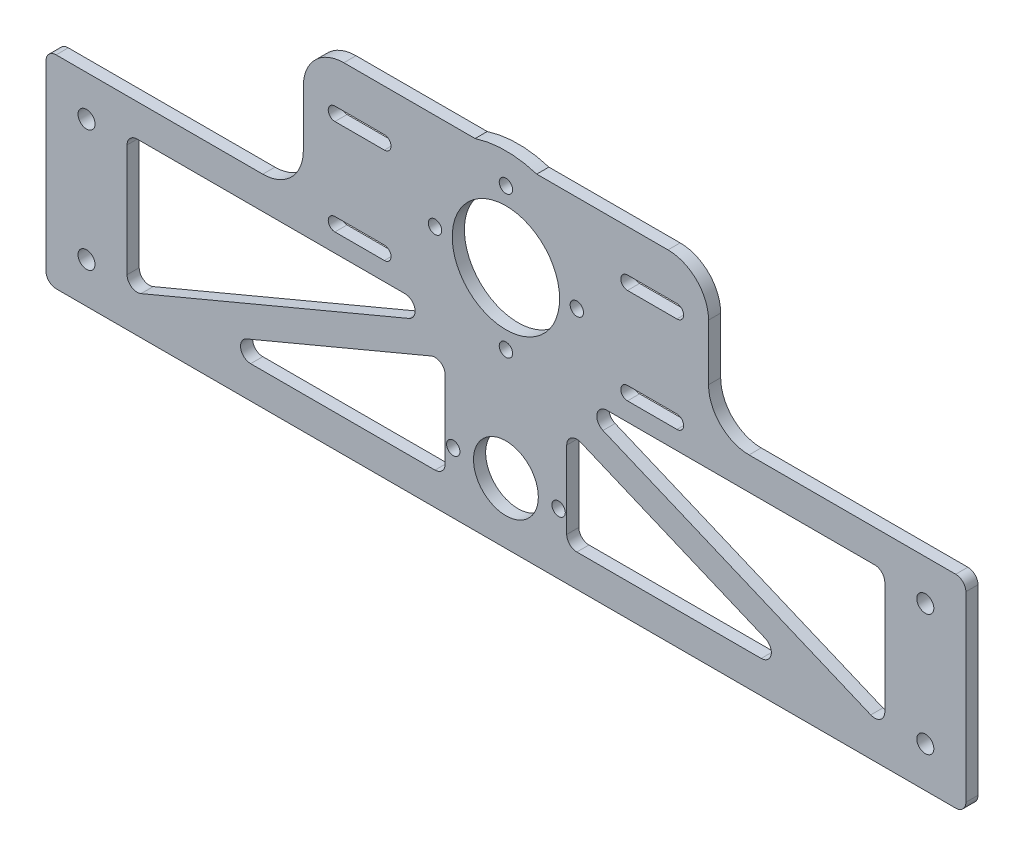
SolidWorks part; units mm, degrees
material "6061 合金"
ref_plane "前视基准面" through (0, 0, 0) normal (0, 0, 1) x (1, 0, 0)
ref_plane "上视基准面" through (0, 0, 0) normal (0, 1, 0) x (1, 0, 0)
ref_plane "右视基准面" through (0, 0, 0) normal (1, 0, 0) x (0, 0, -1)
sketch "草图1" plane through (0, 0, 0) normal (0, 0, 1) x (1, 0, 0)
  line L0 (7.6049, 23.8152) -> (113.5, -10) construction
  line L1 (113.5, -10) -> (113.5, -60)
  line L3 (0, 17.5) -> (0, -70.2013) construction
  line L4 (103.5, -6.8067) -> (103.5, -60) construction
  line L5 (113.5, -35) -> (103.5, -35) construction
  line L6 (-113.5, -35) -> (-103.5, -35) construction
  line L7 (-103.5, -6.8067) -> (-103.5, -60) construction
  line L9 (-113.5, -10) -> (-113.5, -60)
  line L10 (-7.6049, 23.8152) -> (-113.5, -10) construction
  line L11 (-113.5, -10) -> (-50, -10)
  line L12 (-50, -10) -> (-50, 23.8152)
  line L13 (-50, 23.8152) -> (-7.6049, 23.8152)
  line L14 (50, 23.8152) -> (7.6049, 23.8152)
  line L15 (113.5, -10) -> (50, -10)
  line L16 (50, -10) -> (50, 23.8152)
  line L17 (-113.5, -60) -> (113.5, -60)
  circle A0 centre (0, 0) radius 17.5 construction
  circle A1 centre (0, 0) radius 13.25
  circle A2 centre (0, 17.5) radius 1.65
  circle A3 centre (-17.5, 0) radius 1.65
  circle A4 centre (0, -17.5) radius 1.65
  circle A5 centre (17.5, 0) radius 1.65
  arc A6 (7.6049, 23.8152) -> (-7.6049, 23.8152) centre (0, 0) ccw
  circle A7 centre (103.5, -20) radius 2.1
  circle A8 centre (103.5, -50) radius 2.1
  circle A10 centre (0, -45) radius 8
  circle A11 centre (-103.5, -50) radius 2.1
  circle A12 centre (-103.5, -20) radius 2.1
  dimension "D1" = 26.5
  dimension "D2" = 35
  dimension "D3" = 3.3
  dimension "D4" = 4.2
  dimension "D6" = 30
  dimension "D8" = 50
  dimension "D10" = 83.8152
  dimension "D11" = 16
  dimension "D12" = 15
  dimension "D5" = 10
  dimension "D7" = 50
  dimension "D9" = 227
  dimension "D14" = 100
extrude "凸台-拉伸1" add sketch "草图1" along normal blind 3
fillet "圆角1" radius 10 4 edges at (50, -10, 1.5) (50, 23.8152, 1.5) (-50, -10, 1.5) (-50, 23.8152, 1.5)
sketch "草图2" plane through (0, 0, 3) normal (0, 0, 1) x (1, 0, 0)
  line L0 (-93.5, -18) -> (-93.5, -52)
  line L1 (-93.5, -52) -> (-12.5, -18)
  line L2 (-12.5, -18) -> (-93.5, -18)
  line L7 (0, 25) -> (0, -75) construction
  line L8 (12.5, -18) -> (93.5, -18)
  line L9 (93.5, -52) -> (12.5, -18)
  line L10 (93.5, -18) -> (93.5, -52)
  line L12 (113.5, -60) -> (113.5, -10) construction
  line L13 (-75.414, -52) -> (-15, -26.6411)
  line L14 (-15, -26.6411) -> (-15, -52)
  line L15 (-15, -52) -> (-75.414, -52)
  line L16 (15, -52) -> (75.414, -52)
  line L17 (15, -26.6411) -> (15, -52)
  line L18 (75.414, -52) -> (15, -26.6411)
  line L19 (113.5, -10) -> (60, -10) construction
  arc A0 (7.6049, 23.8152) -> (-7.6049, 23.8152) centre (0, 0) ccw construction
  dimension "D4" = 7
  dimension "D1" = 8
  dimension "D2" = 20
  dimension "D3" = 25
  dimension "D5" = 34
  dimension "D6" = 30
extrude "切除-拉伸1" cut sketch "草图2" against normal blind 3
fillet "圆角3" radius 2.5 16 edges at (-113.5, -10, 1.5) (113.5, -10, 1.5) (12.5, -18, 1.5) (93.5, -52, 1.5) (93.5, -18, 1.5) (-93.5, -18, 1.5) (-12.5, -18, 1.5) (-93.5, -52, 1.5) (113.5, -60, 1.5) (-113.5, -60, 1.5) (75.414, -52, 1.5) (15, -26.6411, 1.5) (15, -52, 1.5) (-15, -52, 1.5) (-15, -26.6411, 1.5) (-75.414, -52, 1.5)
sketch "草图3" plane through (0, 0, 3) normal (0, 0, 1) x (1, 0, 0)
  line L0 (-13, -45) -> (13, -45) construction
  line L2 (-111, -60) -> (111, -60) construction
  circle A1 centre (-13, -45) radius 1.65
  circle A2 centre (13, -45) radius 1.65
  circle A5 centre (0, -45) radius 8 construction
  dimension "D3" = 3.3
  dimension "D1" = 15
  dimension "D4" = 13
  dimension "D2" = 26
extrude "切除-拉伸2" cut sketch "草图3" against normal through all
sketch "草图4" plane through (0, 0, 3) normal (0, 0, 1) x (1, 0, 0)
  line L0 (-48.5624, 0) -> (41.9145, 0) construction
  line L1 (0, 25) -> (0, -17.5) construction
  line L2 (-42.2, 11.8) -> (-30, 11.8) construction
  line L3 (-42.2, 13.45) -> (-30, 13.45)
  line L4 (-42.2, 10.15) -> (-30, 10.15)
  line L5 (-42.2, -11.8) -> (-30, -11.8) construction
  line L6 (-42.2, -13.45) -> (-30, -13.45)
  line L7 (-42.2, -10.15) -> (-30, -10.15)
  line L8 (42.2, 11.8) -> (30, 11.8) construction
  line L9 (42.2, 13.45) -> (30, 13.45)
  line L10 (42.2, 10.15) -> (30, 10.15)
  line L11 (42.2, -11.8) -> (30, -11.8) construction
  line L12 (42.2, -13.45) -> (30, -13.45)
  line L13 (42.2, -10.15) -> (30, -10.15)
  arc A0 (7.6049, 23.8152) -> (-7.6049, 23.8152) centre (0, 0) ccw construction
  arc A1 (-42.2, 13.45) -> (-42.2, 10.15) centre (-42.2, 11.8) ccw
  arc A2 (-30, 10.15) -> (-30, 13.45) centre (-30, 11.8) ccw
  arc A3 (-42.2, -13.45) -> (-42.2, -10.15) centre (-42.2, -11.8) cw
  arc A4 (-30, -10.15) -> (-30, -13.45) centre (-30, -11.8) cw
  arc A5 (42.2, 13.45) -> (42.2, 10.15) centre (42.2, 11.8) cw
  arc A6 (30, 10.15) -> (30, 13.45) centre (30, 11.8) cw
  arc A7 (42.2, -13.45) -> (42.2, -10.15) centre (42.2, -11.8) ccw
  arc A8 (30, -10.15) -> (30, -13.45) centre (30, -11.8) ccw
  point P11 (-36.1, 11.8)
  point P18 (-36.1, -11.8)
  point P25 (36.1, 11.8)
  point P32 (36.1, -11.8)
  dimension "D1" = 60
  dimension "D2" = 12.2
  dimension "D3" = 3.3
  dimension "D4" = 20.3
extrude "切除-拉伸3" cut sketch "草图4" against normal through all
